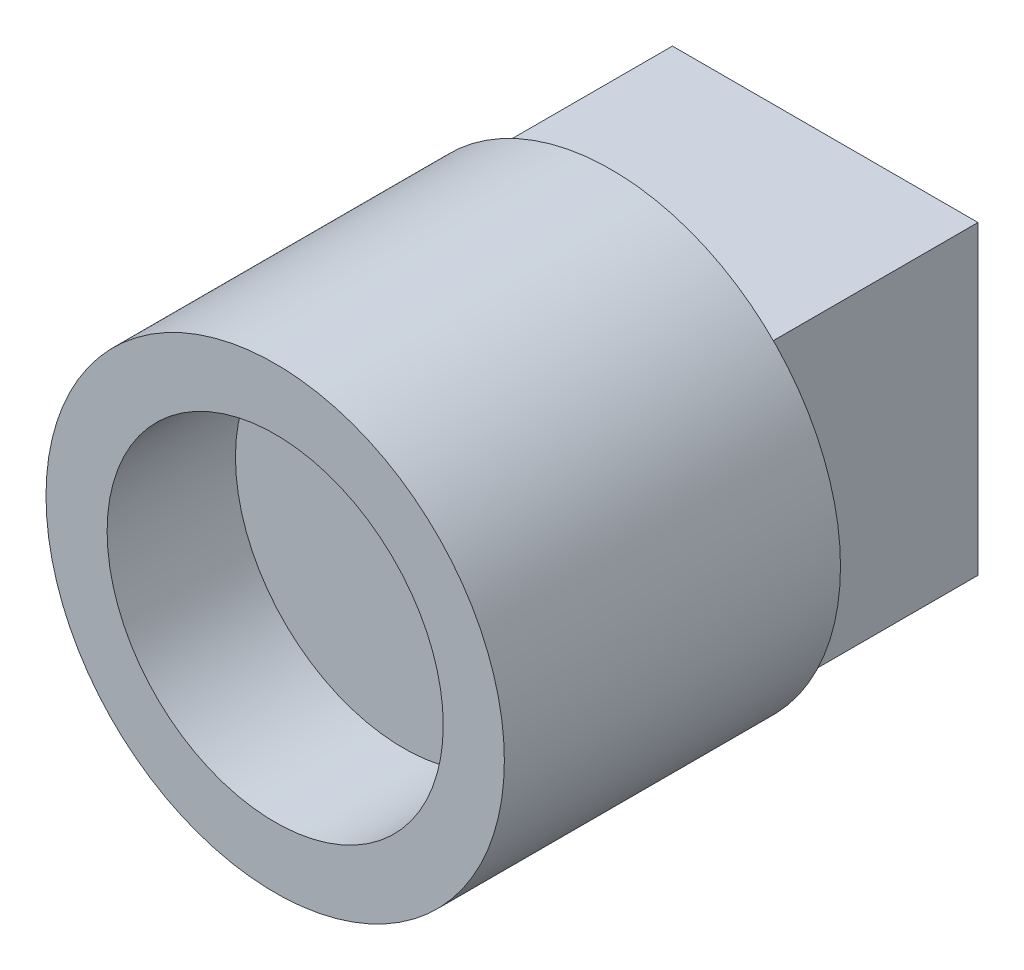
SolidWorks part; units mm, degrees
ref_plane "Front Plane" through (0, 0, 0) normal (0, 0, 1) x (1, 0, 0)
ref_plane "Top Plane" through (0, 0, 0) normal (0, 1, 0) x (1, 0, 0)
ref_plane "Right Plane" through (0, 0, 0) normal (1, 0, 0) x (0, 0, -1)
sketch "Sketch1" plane through (0, 0, 0) normal (0, 0, 1) x (1, 0, 0)
  circle A0 centre (0, 0) radius 75
extrude "Boss-Extrude1" add sketch "Sketch1" along normal blind 110
sketch "Sketch3" plane through (0, 0, 0) normal (0, 0, -1) x (-1, 0, 0)
  line L1 (50, 50) -> (-50, 50)
  line L2 (50, 50) -> (50, -50)
  line L3 (50, -50) -> (-50, -50)
  line L4 (-50, 50) -> (-50, -50)
  line L5 (50, 50) -> (-50, -50) construction
  line L6 (50, -50) -> (-50, 50) construction
  line L7 (53.5607, 52.5) -> (-53.5607, 52.5)
  line L8 (53.5607, 52.5) -> (53.5607, -52.5)
  line L9 (53.5607, -52.5) -> (-53.5607, -52.5)
  line L10 (-53.5607, 52.5) -> (-53.5607, -52.5)
  line L11 (53.5607, 52.5) -> (-53.5607, -52.5) construction
  line L12 (53.5607, -52.5) -> (-53.5607, 52.5) construction
  circle A0 centre (0, 0) radius 75 construction
  point P0 (0, 0)
  point P6 (0, 0)
  dimension "D1" = 100
  dimension "D2" = 100
  dimension "D3" = 2.5
  dimension "D4" = 3.5607
extrude "Boss-Extrude2" add sketch "Sketch3" along normal blind 70 contours L3 L4 L1 L2
sketch "Sketch4" plane through (0, 0, 110) normal (0, 0, 1) x (1, 0, 0)
  circle A0 centre (0, 0) radius 55
extrude "Cut-Extrude1" cut sketch "Sketch4" against normal blind 42
